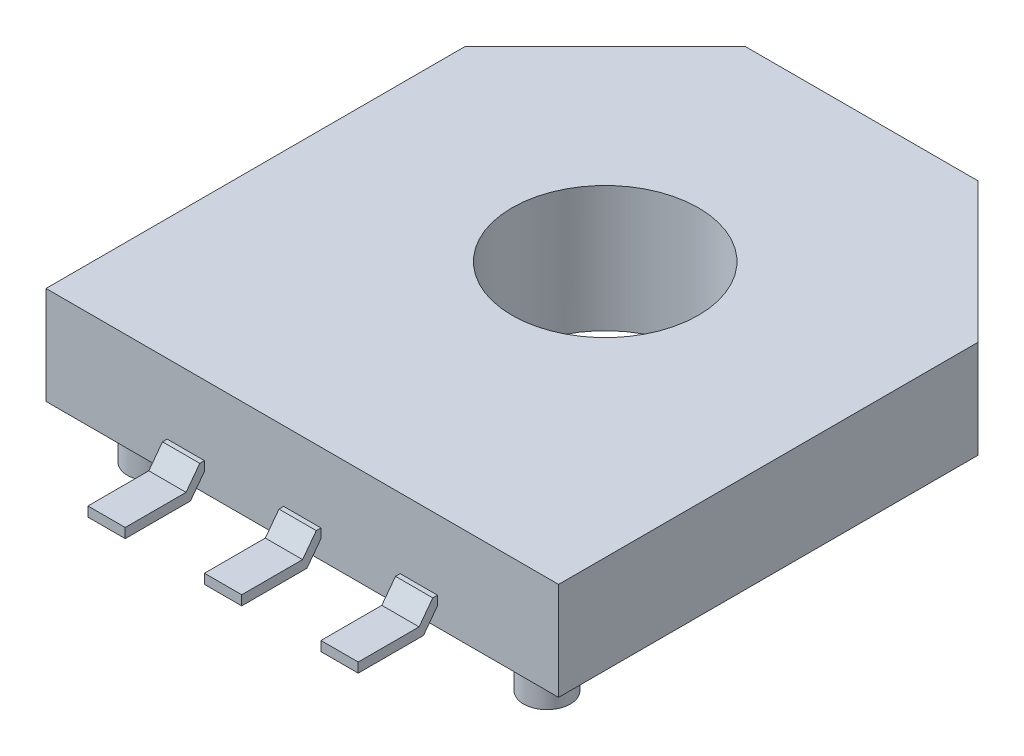
SolidWorks part; units mm, degrees
ref_plane "Front Plane" through (0, 0, 0) normal (0, 0, 1) x (1, 0, 0)
ref_plane "Top Plane" through (0, 0, 0) normal (0, 1, 0) x (1, 0, 0)
ref_plane "Right Plane" through (0, 0, 0) normal (1, 0, 0) x (0, 0, -1)
sketch "Sketch1" plane through (0, 0, 0) normal (0, 1, 0) x (1, 0, 0)
  line L0 (-1000, 0) -> (49000, 0) construction
  line L1 (0, -1000) -> (0, 49000) construction
  line L2 (0, 0) -> (0, -6.5) construction
  line L3 (-5.5, -6.5) -> (5.5, -6.5)
  line L4 (-2.5, 5.5) -> (2.5, 5.5)
  line L5 (5.5, -6.5) -> (5.5, 2.5)
  line L6 (-5.5, -6.5) -> (-5.5, 2.5)
  line L7 (-5.5, 2.5) -> (-2.5, 5.5)
  line L8 (2.5, 5.5) -> (5.5, 2.5)
  circle A0 centre (0, 0) radius 2
  point P11 (0, -6.5)
  point P14 (0, 5.5)
  dimension "D1" = 4
  dimension "D2" = 6.5
  dimension "D3" = 5.5
  dimension "D4" = 9
extrude "Boss-Extrude1" add sketch "Sketch1" along normal blind 2.1
sketch "Sketch2" plane through (0, 0, 0) normal (0, -1, 0) x (1, 0, 0)
  circle A0 centre (0, 0) radius 2
  circle A1 centre (0, 0) radius 2.5
extrude "Boss-Extrude2" add sketch "Sketch2" along normal blind 0.6
sketch "Sketch3" plane through (0, 0, 0) normal (0, -1, 0) x (1, 0, 0)
  line L0 (-4.25, 5.5) -> (4.25, 5.5) construction
  line L2 (0, 201000) -> (0, -249000) construction
  line L3 (-201000, 0) -> (249000, 0) construction
  circle A0 centre (4.25, 5.5) radius 0.5
  circle A1 centre (-4.25, 5.5) radius 0.5
  point P3 (0, 5.5)
  dimension "D2" = 1
  dimension "D1" = 5.5
extrude "Boss-Extrude3" add sketch "Sketch3" along normal blind 1
sketch "Sketch4" plane through (0, 0, 0) normal (1, 0, 0) x (0, 0, -1)
  line L0 (-6.5, 0.6) -> (-6.5, 0.4)
  line L1 (-6.6002, 0.5998) -> (-6.5, 0.6)
  line L3 (-6.8, 0) -> (-8.2, 0)
  line L5 (-201000, 0) -> (249000, 0) construction
  line L6 (-6.5, 2.1) -> (-6.5, 0) construction
  line L7 (-8.2, 0) -> (-8.2, 0.2078)
  line L8 (-6.8, 0) -> (-6.5, 0.4)
  line L9 (-8.2, 0.2078) -> (-6.8941, 0.2078)
  line L10 (-6.6002, 0.5998) -> (-6.8941, 0.2078)
  dimension "D1" = 1.5
  dimension "D2" = 8.2
  dimension "D3" = 0.2
  dimension "D4" = 1.4
  dimension "D5" = 0.2
extrude "Boss-Extrude4" add sketch "Sketch4" along normal mid plane 0.8
ref_plane "Plane1" through (2.5, 0, 0) normal (1, 0, 0) x (0, 0, -1)
ref_plane "Plane2" through (-2.5, 0, 0) normal (1, 0, 0) x (0, 0, -1)
pattern_linear "LPattern1" count 2 spacing 2.5 along (1, 0, 0) count 2 spacing 2.5 along (-1, 0, 0) of "Boss-Extrude4"
ref_plane "Plane3" through (0, 0, 0.5) normal (0, 0, 1) x (1, 0, 0)
mirror "Mirror1" about plane through (0, 0, 0.5) normal (0, 0, 1) of "Boss-Extrude4"
